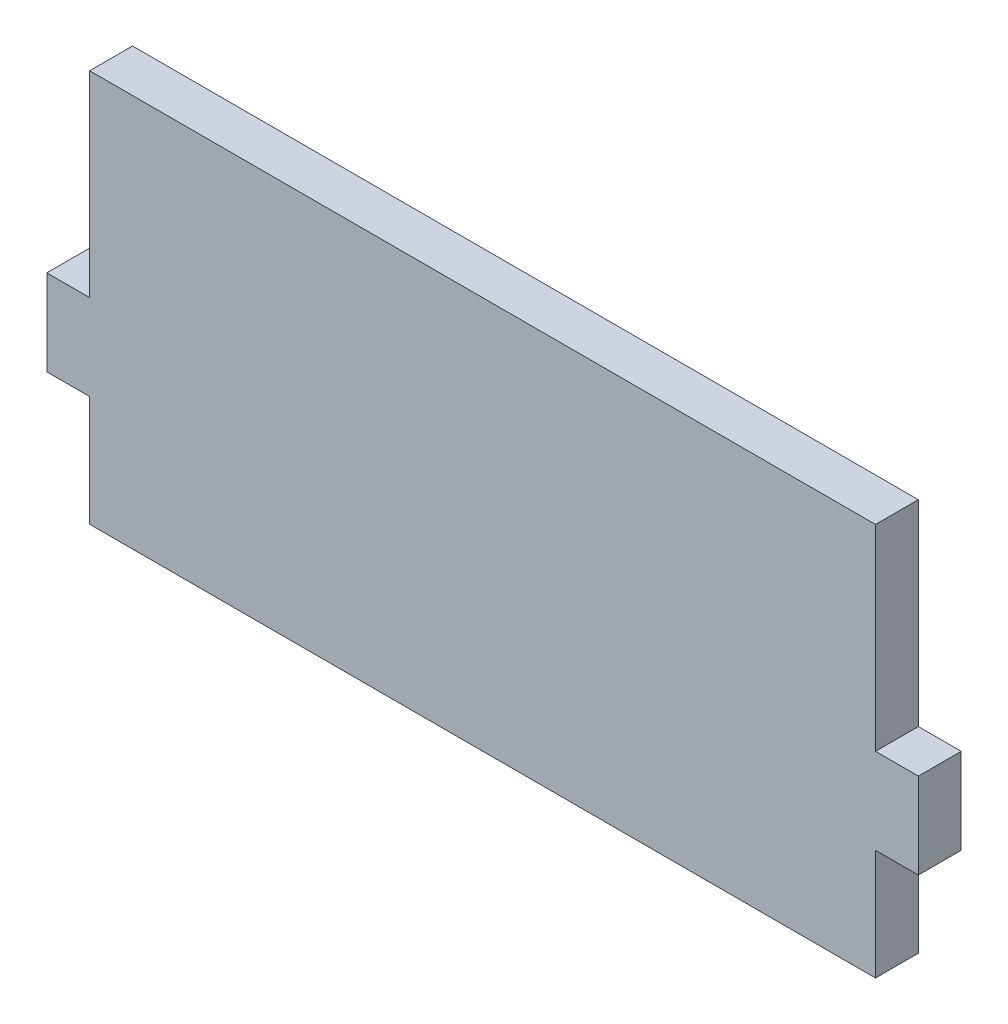
SolidWorks part; units mm, degrees
ref_plane "Přední rovina" through (0, 0, 0) normal (0, 0, 1) x (1, 0, 0)
ref_plane "Horní rovina" through (0, 0, 0) normal (0, 1, 0) x (1, 0, 0)
ref_plane "Pravá rovina" through (0, 0, 0) normal (1, 0, 0) x (0, 0, -1)
sketch "Skica1" plane through (0, 0, 0) normal (0, 0, 1) x (1, 0, 0)
  line L0 (55, -19.75) -> (55, -27.49)
  line L1 (0, 0) -> (55, 0)
  line L2 (0, 0) -> (0, -13.75)
  line L3 (0, -27.49) -> (55, -27.49)
  line L4 (55, 0) -> (55, -13.75)
  line L5 (0, -13.75) -> (-3, -13.75)
  line L6 (0, -19.75) -> (-3, -19.75)
  line L7 (-3, -13.75) -> (-3, -19.75)
  line L8 (55, -13.75) -> (58, -13.75)
  line L9 (55, -19.75) -> (58, -19.75)
  line L10 (58, -13.75) -> (58, -19.75)
  line L11 (0, -19.75) -> (0, -27.49)
  dimension "D1" = 55
  dimension "D2" = 27.49
  dimension "D3" = 13.75
  dimension "D4" = 0
  dimension "D5" = 6
  dimension "D6" = 6
  dimension "D7" = 3
  dimension "D8" = 3
extrude "Přidat vysunutím1" add sketch "Skica1" along normal blind 3
